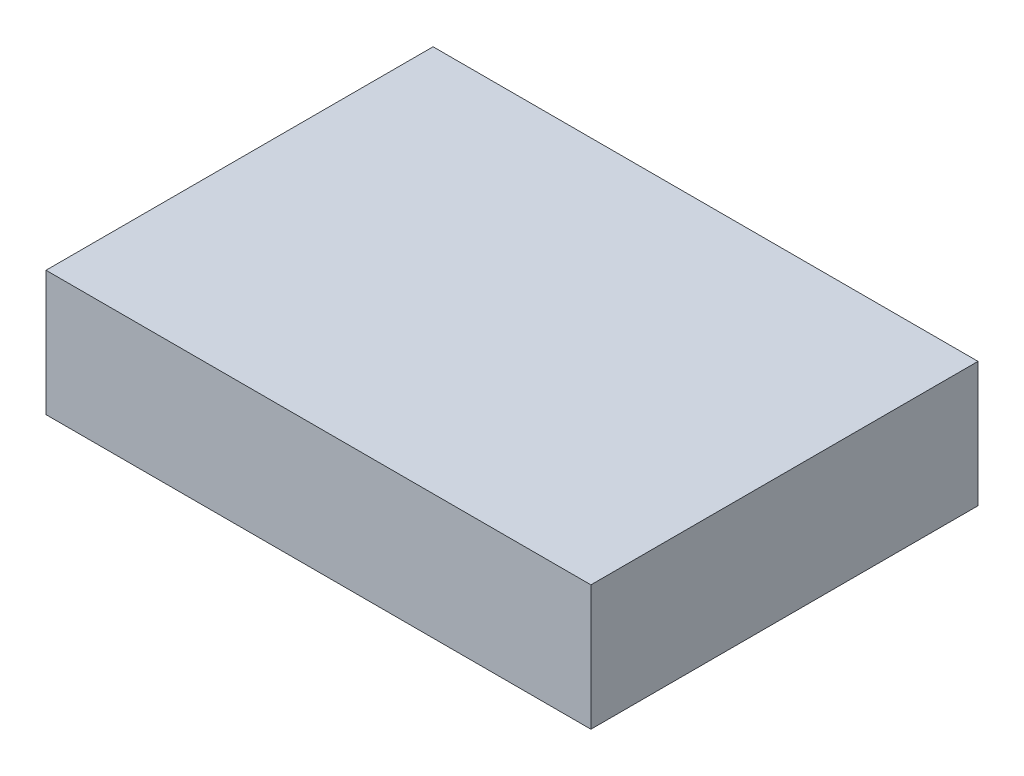
SolidWorks part; units mm, degrees
ref_plane "Front Plane" through (0, 0, 0) normal (0, 0, 1) x (1, 0, 0)
ref_plane "Top Plane" through (0, 0, 0) normal (0, 1, 0) x (1, 0, 0)
ref_plane "Right Plane" through (0, 0, 0) normal (1, 0, 0) x (0, 0, -1)
sketch "Sketch1" plane through (0, 0, 0) normal (0, 1, 0) x (1, 0, 0)
  line L1 (457.5, 0) -> (-457.5, 0)
  line L2 (457.5, 0) -> (457.5, 650)
  line L3 (457.5, 650) -> (-457.5, 650)
  line L4 (-457.5, 0) -> (-457.5, 650)
  dimension "D1" = 915
  dimension "D2" = 650
extrude "Boss-Extrude1" add sketch "Sketch1" against normal blind 210
